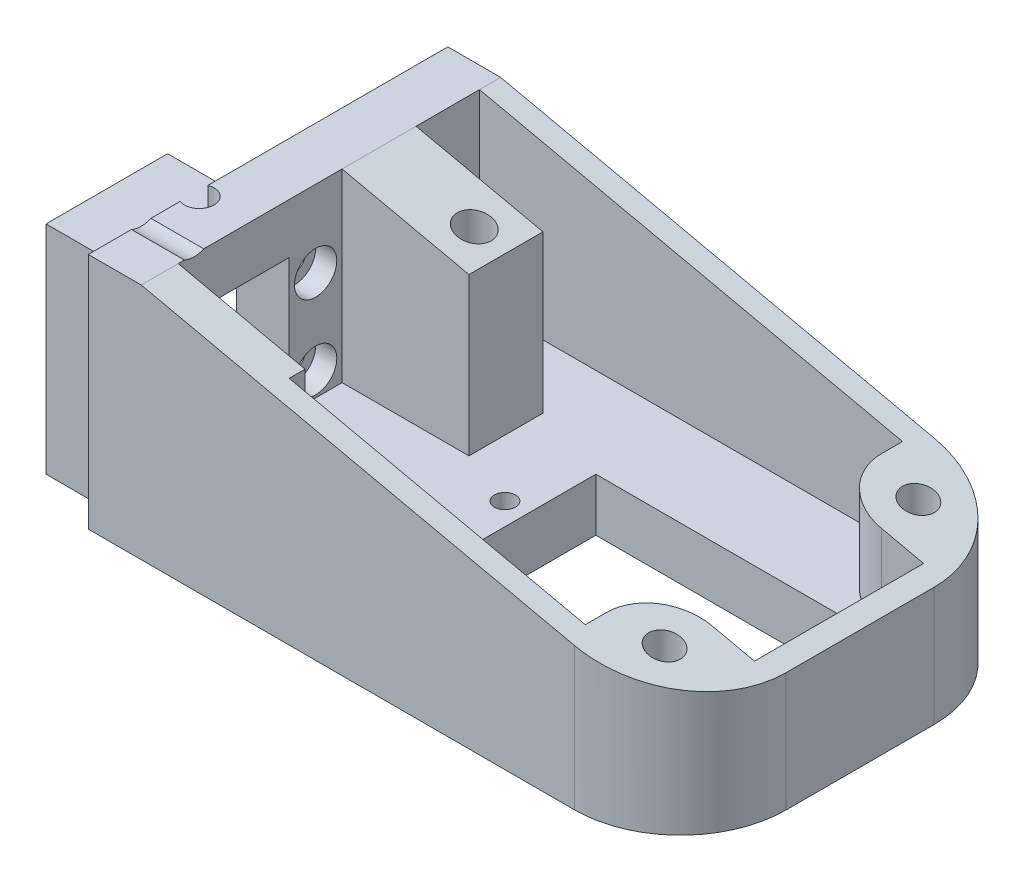
SolidWorks part; units mm, degrees
ref_plane "Front Plane" through (0, 0, 0) normal (0, 0, 1) x (1, 0, 0)
ref_plane "Top Plane" through (0, 0, 0) normal (0, 1, 0) x (1, 0, 0)
ref_plane "Right Plane" through (0, 0, 0) normal (1, 0, 0) x (0, 0, -1)
sketch "Sketch2" plane through (0, 0, 0) normal (0, 1, 0) x (1, 0, 0)
  line L0 (0, 14) -> (0, 0) construction
  line L1 (0, 0) -> (46, 0)
  line L2 (0, 14) -> (0, 34)
  line L3 (0, 34) -> (46, 34)
  line L4 (56, 10) -> (56, 24)
  line L5 (0, 0) -> (-6.5, 0)
  line L7 (0, 14) -> (-6.5, 14)
  line L8 (-6.5, 0) -> (-6.5, 14)
  arc A0 (46, 0) -> (56, 10) centre (46, 10) ccw
  arc A1 (46, 34) -> (56, 24) centre (46, 24) cw
  dimension "D5" = 10
  dimension "D1" = 34
  dimension "D2" = 20
  dimension "D3" = 6.5
  dimension "D4" = 56
extrude "Boss-Extrude1" add sketch "Sketch2" along normal blind 22.5
sketch "Sketch3" plane through (0, 22.5, 0) normal (0, 1, 0) x (1, 0, 0)
  line L0 (46, 34) -> (0, 34) construction
  line L1 (5, 32) -> (45, 32)
  line L2 (5, 32) -> (5, 2)
  line L3 (5, 2) -> (45, 2)
  line L4 (45, 32) -> (45, 30)
  line L5 (50, 25) -> (54, 25)
  line L7 (50, 9) -> (54, 9)
  line L8 (54, 25) -> (54, 9)
  line L9 (-6.5, 0) -> (46, 0) construction
  line L10 (56, 10) -> (56, 24) construction
  line L11 (45, 4) -> (45, 2)
  line L12 (45, 25) -> (45, 9) construction
  line L13 (45, 9) -> (45, 4) construction
  line L14 (0, 34) -> (0, 14) construction
  line L15 (54, 17) -> (56, 17) construction
  line L17 (5, 3.5) -> (17, 3.5)
  line L18 (5, 3.5) -> (5, 2)
  line L19 (5, 2) -> (17, 2)
  line L20 (17, 3.5) -> (17, 2)
  arc A0 (45, 4) -> (50, 9) centre (50, 4) cw
  arc A1 (50, 25) -> (45, 30) centre (50, 30) cw
  dimension "D6" = 5
  dimension "D7" = 12
  dimension "D10" = 1.5
  dimension "D1" = 2
  dimension "D2" = 2
  dimension "D3" = 7
  dimension "D4" = 7
  dimension "D5" = 2
  dimension "D8" = 5
  dimension "D9" = 40
extrude "Cut-Extrude1" cut sketch "Sketch3" against normal blind 17.5 contours L5 A1 L4 L1 L2 L17 L20 L3 L11 A0 L7 L8
sketch "Sketch4" plane through (5, 0, 0) normal (1, 0, 0) x (0, 0, -1)
  line L0 (34, 22.5) -> (34, 0) construction
  line L1 (16.5, 7.25) -> (28.5, 7.25) construction
  line L2 (16.5, 7.25) -> (16.5, 15.25) construction
  line L3 (16.5, 15.25) -> (28.5, 15.25) construction
  line L4 (28.5, 7.25) -> (28.5, 15.25) construction
  line L5 (16.5, 7.25) -> (28.5, 15.25) construction
  line L6 (16.5, 15.25) -> (28.5, 7.25) construction
  line L7 (34, 0) -> (14, 0) construction
  circle A0 centre (28.5, 15.25) radius 1
  circle A1 centre (28.5, 7.25) radius 1
  circle A2 centre (16.5, 7.25) radius 1
  circle A3 centre (16.5, 15.25) radius 1
  point P0 (22.5, 11.25)
  dimension "D6" = 2
  dimension "D7" = 2
  dimension "D8" = 2
  dimension "D9" = 2
  dimension "D1" = 12
  dimension "D2" = 12
  dimension "D3" = 5.5
  dimension "D4" = 7.25
  dimension "D5" = 8
extrude "Cut-Extrude2" cut sketch "Sketch4" against normal through all and the other way blind 15
sketch "Sketch5" plane through (-6.5, 0, 0) normal (-1, 0, 0) x (0, 0, 1)
  line L0 (-14, 0) -> (0, 0) construction
  line L1 (-3.5, 17.75) -> (-14, 17.75)
  line L2 (-3.5, 17.75) -> (-3.5, 5.25)
  line L3 (-3.5, 5.25) -> (-14, 5.25)
  line L4 (-14, 17.75) -> (-14, 5.25)
  line L5 (-14, 22.5) -> (-14, 0) construction
  dimension "D2" = 10.5
  dimension "D3" = 5.25
  dimension "D4" = 12.5
extrude "Cut-Extrude3" cut sketch "Sketch5" against normal blind 20
sketch "Sketch6" plane through (0, 22.5, 0) normal (0, 1, 0) x (1, 0, 0)
  line L0 (-6.5, 14) -> (-6.5, 0) construction
  line L1 (-6.5, 0) -> (46, 0) construction
  circle A0 centre (0.5, 10) radius 1.4
  point P4 (-6.5, 7)
  dimension "D1" = 2.8
  dimension "D2" = 7
  dimension "D3" = 10
extrude "Cut-Extrude4" cut sketch "Sketch6" against normal blind 10
sketch "Sketch8" plane through (0, 5, 0) normal (0, 1, 0) x (1, 0, 0)
  line L0 (48.5, 17) -> (54, 17) construction
  line L1 (24.5, 23.5) -> (48.5, 23.5)
  line L2 (24.5, 23.5) -> (24.5, 10.5)
  line L3 (24.5, 10.5) -> (48.5, 10.5)
  line L4 (48.5, 23.5) -> (48.5, 10.5)
  line L5 (54, 9) -> (54, 25) construction
  line L6 (24.5, 17) -> (21.4, 17) construction
  circle A0 centre (50.6, 17) radius 1
  circle A1 centre (22.4, 17) radius 1
  dimension "D4" = 2
  dimension "D5" = 2
  dimension "D7" = 2.1
  dimension "D1" = 13
  dimension "D2" = 24
  dimension "D3" = 5.5
  dimension "D6" = 2.1
extrude "Cut-Extrude6" cut sketch "Sketch8" against normal through all
sketch "Sketch9" plane through (0, 22.5, 0) normal (0, 1, 0) x (1, 0, 0)
  line L0 (49.5, 29) -> (49.5, 5) construction
  line L1 (49.5, 17) -> (54, 17) construction
  line L2 (54, 9) -> (54, 25) construction
  circle A0 centre (49.5, 29) radius 1.5
  circle A1 centre (49.5, 5) radius 1.5
  dimension "D2" = 3
  dimension "D3" = 3
  dimension "D1" = 24
  dimension "D4" = 4.5
extrude "Cut-Extrude7" cut sketch "Sketch9" against normal through all
sketch "Sketch10" plane through (0, 0, 0) normal (0, -1, 0) x (1, 0, 0)
  circle A0 centre (49.5, -5) radius 3
  circle A1 centre (49.5, -29) radius 3
  dimension "D1" = 6
  dimension "D2" = 6
extrude "Cut-Extrude8" cut sketch "Sketch10" against normal blind 5
ref_plane "Plane1" through (0, 0, -22.5) normal (0, 0, 1) x (1, 0, 0)
sketch "Sketch14" plane through (0, 0, -22.5) normal (0, 0, 1) x (1, 0, 0)
  line L0 (5, 22.5) -> (5, 5)
  line L2 (5, 5) -> (5, 22.5) construction
  line L3 (5, 5) -> (17, 5)
  line L5 (-6.5, 0) -> (46, 0) construction
  line L6 (5, 22.5) -> (17, 22.5)
  line L7 (5, 22.5) -> (45, 22.5) construction
  line L8 (17, 22.5) -> (17, 5)
  dimension "D1" = 12
  dimension "D2" = 5
extrude "Boss-Extrude3" add sketch "Sketch14" along normal mid plane 7
sketch "Sketch11" plane through (0, 0, 0) normal (0, -1, 0) x (1, 0, 0)
  line L0 (8, -8) -> (8, -26) construction
  line L1 (8, -17) -> (56, -17) construction
  line L3 (56, -10) -> (56, -24) construction
  line L4 (-6.5, 0) -> (46, 0) construction
  line L5 (46, -34) -> (0, -34) construction
  circle A0 centre (8, -8) radius 1.5
  circle A1 centre (8, -26) radius 1.5
  dimension "D3" = 3
  dimension "D4" = 3
  dimension "D1" = 18
  dimension "D2" = 48
extrude "Cut-Extrude9" cut sketch "Sketch11" against normal blind 10
sketch "Sketch16" plane through (5, 0, 0) normal (1, 0, 0) x (0, 0, -1)
  circle A0 centre (28.5, 15.25) radius 2
  circle A1 centre (28.5, 7.25) radius 2
  circle A2 centre (16.5, 7.25) radius 2
  circle A3 centre (16.5, 15.25) radius 2
  dimension "D1" = 4
  dimension "D2" = 4
  dimension "D3" = 4
  dimension "D4" = 4
extrude "Cut-Extrude11" cut sketch "Sketch16" against normal blind 2
sketch "Sketch18" plane through (0, 22.5, 0) normal (0, 1, 0) x (1, 0, 0)
  line L1 (-6.5, 0) -> (0, 0)
  line L2 (-6.5, 0) -> (-6.5, 2.5)
  line L3 (-6.5, 2.5) -> (0, 2.5)
  line L4 (0, 0) -> (0, 2.5)
  dimension "D1" = 6.5
  dimension "D2" = 2.5
extrude "Cut-Extrude12" cut sketch "Sketch18" against normal through all
sketch "Sketch21" plane through (0, 0, 0) normal (0, 0, 1) x (1, 0, 0)
  line L0 (5, 22.5) -> (56, 11.25)
  line L1 (56, 22.5) -> (56, 0) construction
  line L2 (56, 11.25) -> (56, 22.5)
  line L3 (56, 22.5) -> (5, 22.5)
  dimension "D1" = 11.25
extrude "Cut-Extrude14" cut sketch "Sketch21" against normal through all
sketch "Sketch22" plane through (0, 0, 0) normal (0, -1, 0) x (1, 0, 0)
  line L0 (14, -22.5) -> (17, -22.5) construction
  line L1 (17, -19) -> (17, -26) construction
  circle A0 centre (14, -22.5) radius 1.6
  dimension "D1" = 3.2
  dimension "D2" = 3
extrude "Cut-Extrude15" cut sketch "Sketch22" against normal through all
sketch "Sketch23" plane through (0, 0, 0) normal (0, -1, 0) x (1, 0, 0)
  circle A0 centre (14, -22.5) radius 3
  dimension "D1" = 6
extrude "Cut-Extrude18" cut sketch "Sketch23" against normal blind 3
sketch "Sketch25" plane through (0, 22.5, 0) normal (0, 1, 0) x (1, 0, 0)
  line L0 (0, 14) -> (-6.5, 14) construction
  line L1 (-6.5, 14) -> (0, 14)
  line L2 (-6.5, 14) -> (-6.5, 2.5)
  line L3 (-6.5, 2.5) -> (0, 2.5)
  line L4 (0, 14) -> (0, 2.5)
  line L5 (-6.5, 14) -> (-6.5, 2.5) construction
  line L6 (0, 0) -> (0, 2.5) construction
sketch "Sketch26" plane through (0, 0, 0) normal (-1, 0, 0) x (0, 0, 1)
  line L0 (-14, 22.5) -> (-2.5, 22.5) construction
  line L1 (-5.9165, 22.5) -> (-4.0835, 22.5)
  line L2 (0, 0) -> (0, 22.5) construction
  arc A0 (-5.9165, 22.5) -> (-4.0835, 22.5) centre (-5, 24.5) ccw
  dimension "D1" = 2
  dimension "D2" = 2.2
  dimension "D3" = 5
  dimension "D4" = 2
extrude "Cut-Extrude19" cut sketch "Sketch26" against normal blind 10
extrude "Cut-Extrude20" cut sketch "Sketch25" against normal blind 2
